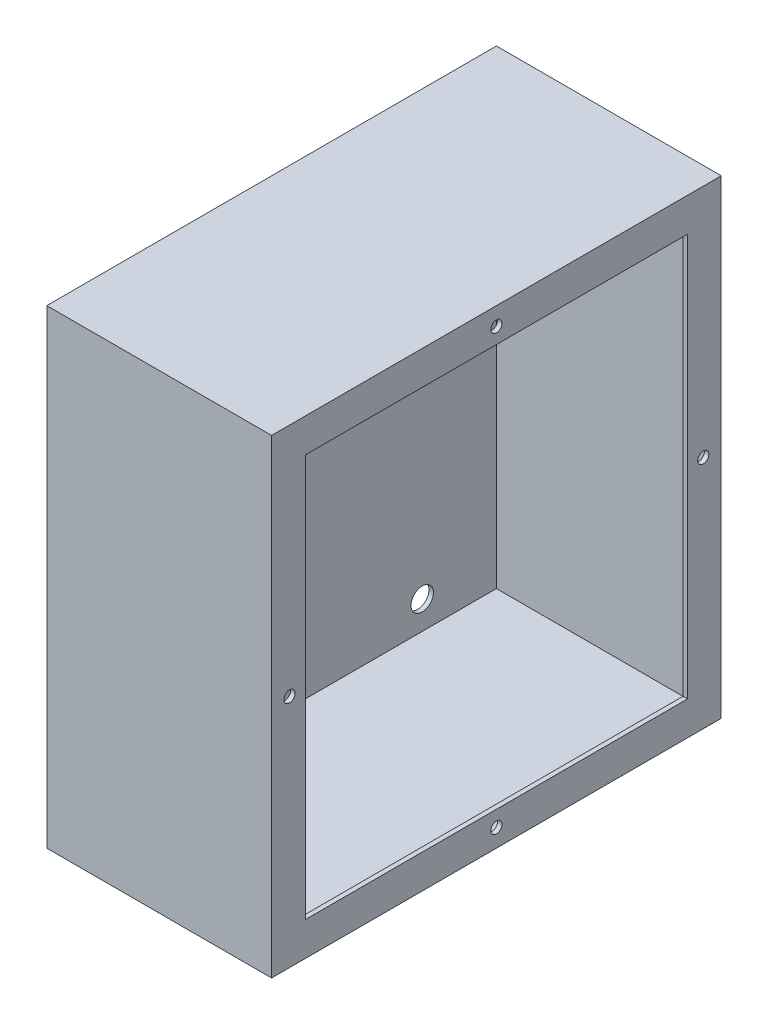
SolidWorks part; units mm, degrees
ref_plane "前视基准面" through (0, 0, 0) normal (0, 0, 1) x (1, 0, 0)
ref_plane "上视基准面" through (0, 0, 0) normal (0, 1, 0) x (1, 0, 0)
ref_plane "右视基准面" through (0, 0, 0) normal (1, 0, 0) x (0, 0, -1)
other "Configuration Table"
sketch "草图1" plane through (0, 0, 0) normal (1, 0, 0) x (0, 0, -1)
  line L1 (-100, 104.5) -> (100, 104.5)
  line L2 (-100, 104.5) -> (-100, -104.5)
  line L3 (-100, -104.5) -> (100, -104.5)
  line L4 (100, 104.5) -> (100, -104.5)
  line L5 (-100, 104.5) -> (100, -104.5) construction
  line L6 (-100, -104.5) -> (100, 104.5) construction
  point P0 (0, 0)
  dimension "D1" = 200
  dimension "D2" = 209
extrude "凸台-拉伸1" add sketch "草图1" along normal blind 100
shell "抽壳1" thickness 2
sketch "草图2" plane through (100, 0, 0) normal (1, 0, 0) x (0, 0, -1)
  line L1 (-85, 89.5) -> (85, 89.5)
  line L2 (-85, 89.5) -> (-85, -89.5)
  line L3 (-85, -89.5) -> (85, -89.5)
  line L4 (85, 89.5) -> (85, -89.5)
  line L5 (-85, 89.5) -> (85, -89.5) construction
  line L6 (-85, -89.5) -> (85, 89.5) construction
  point P0 (0, 0)
  dimension "D1" = 170
  dimension "D2" = 179
extrude "切除-拉伸1" cut sketch "草图2" against normal up to next
sketch "草图3" plane through (100, 0, 0) normal (1, 0, 0) x (0, 0, -1)
  line L0 (-100, 0) -> (0, 0) construction
  line L1 (-100, 104.5) -> (-100, -104.5) construction
  line L2 (0, 0) -> (0, 104.5) construction
  line L3 (100, 104.5) -> (-100, 104.5) construction
  line L4 (100, -104.5) -> (100, 104.5) construction
  circle A0 centre (0, 96.5) radius 2.5
  circle A1 centre (-92, 0) radius 2.5
  circle A2 centre (0, -96.5) radius 2.5
  circle A3 centre (92, 0) radius 2.5
  dimension "D1" = 5
  dimension "D3" = 193
  dimension "D2" = 8
extrude "切除-拉伸2" cut sketch "草图3" against normal up to next
sketch "草图4" plane through (0, 0, 0) normal (-1, 0, 0) x (0, 0, 1)
  line L0 (-100, 0) -> (0, 0) construction
  line L1 (-100, -104.5) -> (-100, 104.5) construction
  line L2 (0, 0) -> (0, 104.5) construction
  line L3 (-100, 104.5) -> (100, 104.5) construction
  circle A0 centre (-65, 90) radius 5
  circle A1 centre (65, 90) radius 5
  circle A2 centre (-65, -90) radius 5
  circle A3 centre (65, -90) radius 5
  dimension "D1" = 10
  dimension "D2" = 130
  dimension "D3" = 180
extrude "切除-拉伸3" cut sketch "草图4" against normal up to next
